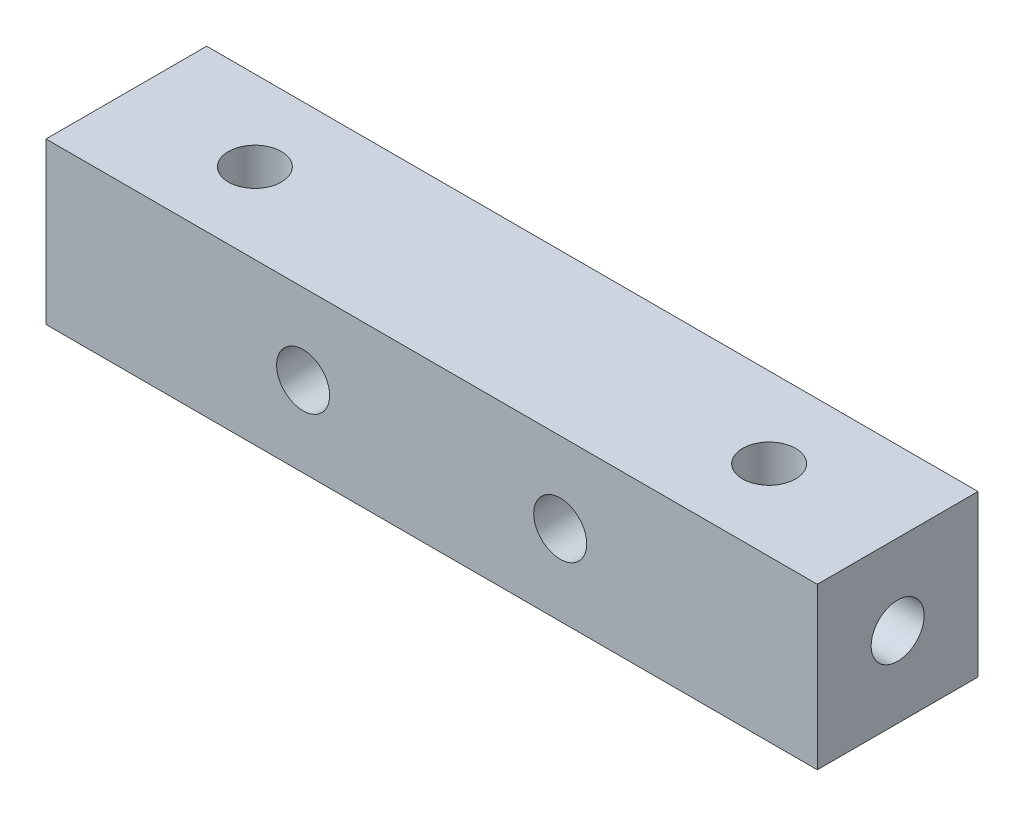
SolidWorks part; units mm, degrees
material "6061 合金"
ref_plane "前视基准面" through (0, 0, 0) normal (0, 0, 1) x (1, 0, 0)
ref_plane "上视基准面" through (0, 0, 0) normal (0, 1, 0) x (1, 0, 0)
ref_plane "右视基准面" through (0, 0, 0) normal (1, 0, 0) x (0, 0, -1)
sketch "草图1" plane through (0, 0, 0) normal (0, 0, 1) x (1, 0, 0)
  line L1 (24, -5) -> (-24, -5)
  line L2 (24, -5) -> (24, 5)
  line L3 (24, 5) -> (-24, 5)
  line L4 (-24, -5) -> (-24, 5)
  line L5 (24, -5) -> (-24, 5) construction
  line L6 (24, 5) -> (-24, -5) construction
  point P0 (0, 0)
  dimension "D1" = 48
  dimension "D2" = 10
extrude "凸台-拉伸1" add sketch "草图1" along normal blind 10
sketch "草图2" plane through (-24, 0, 0) normal (-1, 0, 0) x (0, 0, 1)
  line L0 (0, -5) -> (10, 5) construction
  line L1 (10, -5) -> (0, 5) construction
  point P8 (5, 0)
sketch "草图3" plane through (0, 0, 0) normal (0, 0, -1) x (-1, 0, 0)
  line L0 (24, 5) -> (24, -5) construction
  line L1 (-24, -5) -> (-24, 5) construction
  point P0 (8, 0)
  point P1 (-8, 0)
  dimension "D1" = 16
  dimension "D2" = 16
sketch "草图4" plane through (0, 5, 0) normal (0, 1, 0) x (1, 0, 0)
  line L0 (-24, -10) -> (-24, 0) construction
  line L1 (24, -10) -> (24, 0) construction
  point P0 (-16, -5)
  point P1 (16, -5)
  dimension "D1" = 8
  dimension "D2" = 8
hole_wizard "M4 螺纹孔的螺纹孔钻头1" positions "3D草图2" profile "草图5" hole size "M4" standard "DIN" end condition through all
sketch3d "3D草图2"
  point P0 (-24, 0, 5)
sketch "草图5" plane through (-24, 0, 5) normal (0, 1, 0) x (0, 0, 1)
  line L0 (0, 0) -> (0, 48)
  line L1 (0, 48) -> (1.65, 48)
  line L2 (1.65, 48) -> (1.65, 0)
  line L5 (1.65, 0) -> (0, 0)
  line L11 (0, -6.35) -> (0, 107.95) construction
  dimension "通孔孔直径" = 3.3
  dimension "通孔孔深度" = 48
hole_wizard "M4 螺纹孔的螺纹孔钻头2" positions "3D草图3" profile "草图6" hole size "M4" standard "DIN" end condition through all
sketch3d "3D草图3"
  point P0 (8, 0, 0)
sketch "草图6" plane through (8, 0, 0) normal (1, 0, 0) x (0, 1, 0)
  line L0 (0, 0) -> (0, 10)
  line L1 (0, 10) -> (1.65, 10)
  line L2 (1.65, 10) -> (1.65, 0)
  line L5 (1.65, 0) -> (0, 0)
  line L11 (0, -6.35) -> (0, 107.95) construction
  dimension "通孔孔直径" = 3.3
  dimension "通孔孔深度" = 10
hole_wizard "M4 螺纹孔的螺纹孔钻头3" positions "3D草图4" profile "草图7" hole size "M4" standard "DIN" end condition through all
sketch3d "3D草图4"
  point P0 (-8, 0, 0)
sketch "草图7" plane through (-8, 0, 0) normal (1, 0, 0) x (0, 1, 0)
  line L0 (0, 0) -> (0, 10)
  line L1 (0, 10) -> (1.65, 10)
  line L2 (1.65, 10) -> (1.65, 0)
  line L5 (1.65, 0) -> (0, 0)
  line L11 (0, -6.35) -> (0, 107.95) construction
  dimension "通孔孔直径" = 3.3
  dimension "通孔孔深度" = 10
hole_wizard "M4 螺纹孔的螺纹孔钻头4" positions "3D草图5" profile "草图8" hole size "M4" standard "DIN" end condition through all
sketch3d "3D草图5"
  point P0 (16, 5, 5)
sketch "草图8" plane through (16, 5, 5) normal (1, 0, 0) x (0, 0, 1)
  line L0 (0, 0) -> (0, 10)
  line L1 (0, 10) -> (1.65, 10)
  line L2 (1.65, 10) -> (1.65, 0)
  line L5 (1.65, 0) -> (0, 0)
  line L11 (0, -6.35) -> (0, 107.95) construction
  dimension "通孔孔直径" = 3.3
  dimension "通孔孔深度" = 10
hole_wizard "M4 螺纹孔的螺纹孔钻头5" positions "3D草图6" profile "草图9" hole size "M4" standard "DIN" end condition through all
sketch3d "3D草图6"
  point P0 (-16, 5, 5)
sketch "草图9" plane through (-16, 5, 5) normal (1, 0, 0) x (0, 0, 1)
  line L0 (0, 0) -> (0, 10)
  line L1 (0, 10) -> (1.65, 10)
  line L2 (1.65, 10) -> (1.65, 0)
  line L5 (1.65, 0) -> (0, 0)
  line L11 (0, -6.35) -> (0, 107.95) construction
  dimension "通孔孔直径" = 3.3
  dimension "通孔孔深度" = 10
